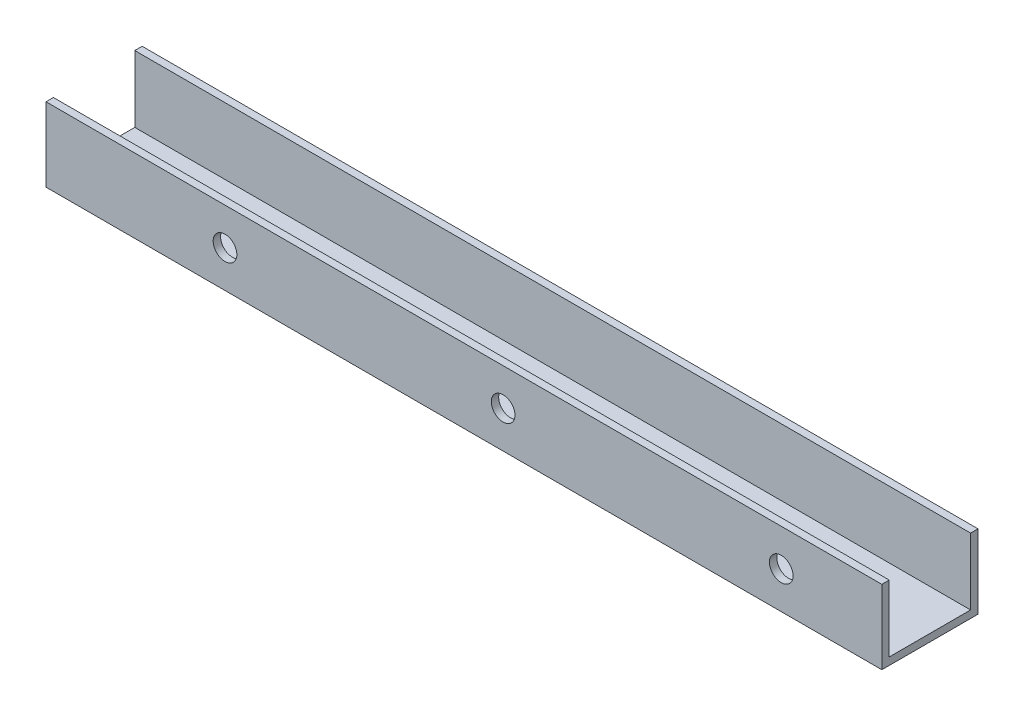
SolidWorks part; units mm, degrees
ref_plane "Plan de face" through (0, 0, 0) normal (0, 0, 1) x (1, 0, 0)
ref_plane "Plan de dessus" through (0, 0, 0) normal (0, 1, 0) x (1, 0, 0)
ref_plane "Plan de droite" through (0, 0, 0) normal (1, 0, 0) x (0, 0, -1)
sketch "Esquisse1" plane through (0, 0, 0) normal (0, 1, 0) x (1, 0, 0)
  line L0 (0, 0) -> (0, 13)
  line L1 (0, 13) -> (113, 13)
  line L2 (113, 13) -> (113, 0)
  line L3 (113, 0) -> (0, 0)
  circle A0 centre (79, 6.5) radius 1.6
  circle A1 centre (29.5, 6.5) radius 1.6
  dimension "D3" = 3.2
  dimension "D1" = 13
  dimension "D2" = 113
  dimension "D4" = 34
  dimension "D5" = 49.5
  dimension "D6" = 6.5
extrude "Boss.-Extru.1" add sketch "Esquisse1" along normal blind 1
sketch "Esquisse2" plane through (0, 1, 0) normal (0, 1, 0) x (1, 0, 0)
  line L0 (0, 13) -> (0, 12)
  line L1 (0, 13) -> (0, 0) construction
  line L2 (0, 12) -> (113, 12)
  line L3 (113, 0) -> (113, 13) construction
  line L4 (113, 12) -> (113, 13)
  line L5 (113, 13) -> (0, 13)
  line L6 (0, 6.5) -> (113, 6.5) construction
  line L7 (113, 0) -> (0, 0)
  line L8 (113, 1) -> (113, 0)
  line L9 (0, 1) -> (113, 1)
  line L10 (0, 0) -> (0, 1)
  dimension "D1" = 1
extrude "Boss.-Extru.2" add sketch "Esquisse2" along normal blind 9
sketch "Esquisse3" plane through (0, 0, 0) normal (0, 0, 1) x (1, 0, 0)
  circle A0 centre (99.4, 5) radius 1.6
  circle A1 centre (61.8, 5) radius 1.6
  circle A2 centre (24.2, 5) radius 1.6
  dimension "D3" = 3.2
  dimension "D1" = 13.6
  dimension "D2" = 5
  dimension "D5" = 37.6
  dimension "D4" = 3
extrude "Enlèv. mat.-Extru.1" cut sketch "Esquisse3" against normal up to next
